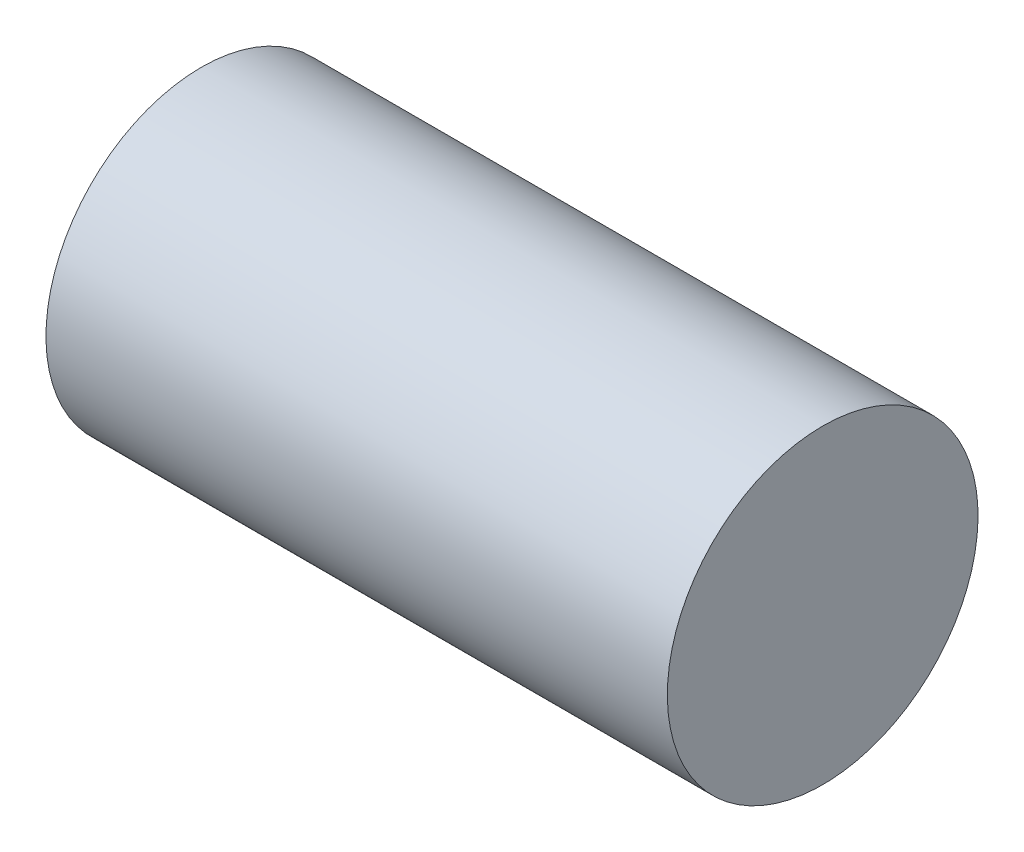
SolidWorks part; units mm, degrees
ref_plane "Front Plane" through (0, 0, 0) normal (0, 0, 1) x (1, 0, 0)
ref_plane "Top Plane" through (0, 0, 0) normal (0, 1, 0) x (1, 0, 0)
ref_plane "Right Plane" through (0, 0, 0) normal (1, 0, 0) x (0, 0, -1)
sketch "Sketch1" plane through (0, 0, 0) normal (0, 0, 1) x (1, 0, 0)
  line L1 (0, 0) -> (-4, 0)
  line L2 (0, 0) -> (0, 1)
  line L3 (0, 1) -> (-4, 1)
  line L4 (-4, 0) -> (-4, 1)
  dimension "D1" = 4
  dimension "D2" = 1
revolve "Revolve1" add sketch "Sketch1" angle 360 about L1
